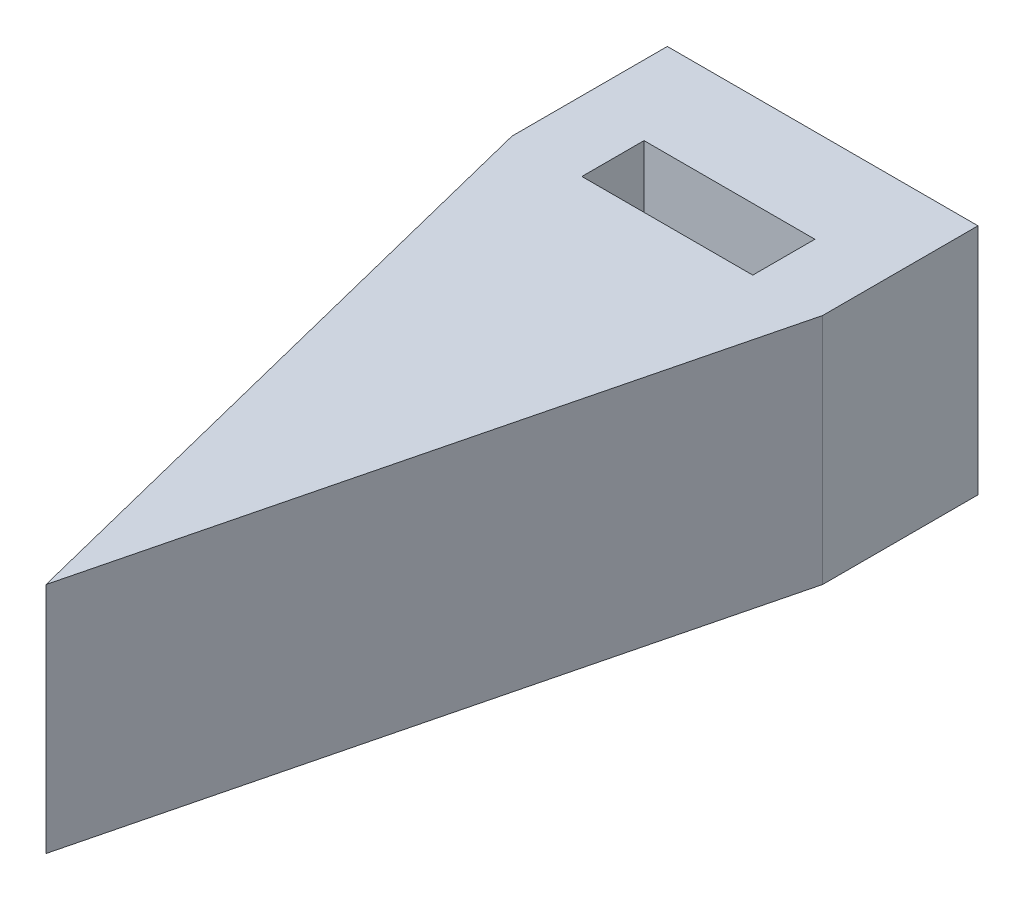
SolidWorks part; units mm, degrees
ref_plane "Front Plane" through (0, 0, 0) normal (0, 0, 1) x (1, 0, 0)
ref_plane "Top Plane" through (0, 0, 0) normal (0, 1, 0) x (1, 0, 0)
ref_plane "Right Plane" through (0, 0, 0) normal (1, 0, 0) x (0, 0, -1)
sketch "Sketch2" plane through (0, 0, 0) normal (0, 1, 0) x (1, 0, 0)
  line L7 (-5, -5) -> (0, -25)
  line L13 (0, 0) -> (0, -25) construction
  line L17 (-5, 0) -> (5, 0)
  line L23 (5, -5) -> (0, -25)
  line L27 (-2.75, -3) -> (2.75, -3)
  line L28 (-2.75, -3) -> (-2.75, -5)
  line L29 (-2.75, -5) -> (2.75, -5)
  line L30 (2.75, -3) -> (2.75, -5)
  line L34 (-5, 0) -> (-5, -5)
  line L35 (5, 0) -> (5, -5)
  point P10 (0, -5)
  dimension "D1" = 2
  dimension "D2" = 10
  dimension "D3" = 3
  dimension "D4" = 5.5
  dimension "D5" = 10
  dimension "D6" = 20
extrude "Body" add sketch "Sketch2" along normal mid plane 7.5
